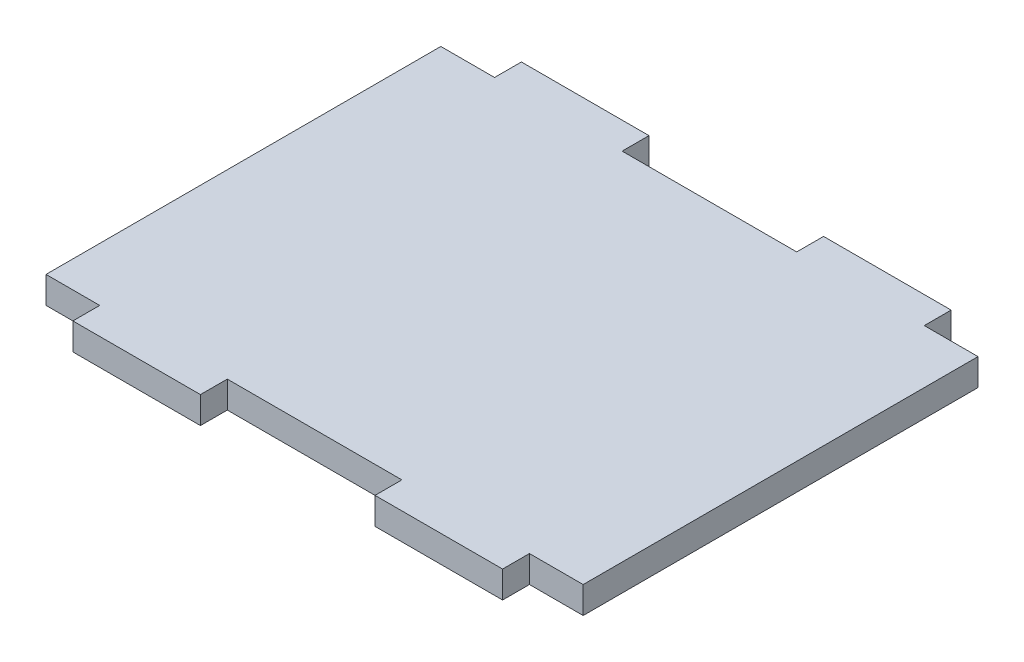
SolidWorks part; units mm, degrees
ref_plane "Front" through (0, 0, 0) normal (0, 0, 1) x (1, 0, 0)
ref_plane "Top" through (0, 0, 0) normal (0, 1, 0) x (1, 0, 0)
ref_plane "Right" through (0, 0, 0) normal (1, 0, 0) x (0, 0, -1)
sketch "Sketch1" plane through (0, 0, 0) normal (0, 1, 0) x (1, 0, 0)
  line L0 (-16, 16.7) -> (-16, 14.7)
  line L1 (20, -16.7) -> (-20, -16.7)
  line L2 (20, -16.7) -> (20, 16.7)
  line L3 (20, 16.7) -> (-20, 16.7)
  line L4 (-20, -16.7) -> (-20, 16.7)
  line L5 (20, -16.7) -> (-20, 16.7) construction
  line L6 (20, 16.7) -> (-20, -16.7) construction
  line L7 (-20, 16.7) -> (20, 16.7)
  line L8 (-20, 16.7) -> (-20, 14.7)
  line L9 (-20, 14.7) -> (20, 14.7)
  line L10 (20, 16.7) -> (20, 14.7)
  line L11 (0, 14.7) -> (0, 16.7) construction
  line L12 (-20, 15.7) -> (20, 15.7) construction
  line L13 (-6.5, 16.7) -> (-6.5, 14.7)
  line L14 (0, 0) -> (-20, 0) construction
  line L15 (0, 0) -> (0, -16.7) construction
  line L16 (6.5, 16.7) -> (6.5, 14.7)
  line L17 (16, 16.7) -> (16, 14.7)
  line L18 (16, -16.7) -> (16, -14.7)
  line L19 (6.5, -16.7) -> (6.5, -14.7)
  line L20 (-6.5, -16.7) -> (-6.5, -14.7)
  line L21 (-16, -16.7) -> (-16, -14.7)
  line L22 (-20, -14.7) -> (20, -14.7)
  point P0 (0, 0)
  point P120 (0, 15.7)
  dimension "D1" = 40
  dimension "D2" = 33.4
  dimension "D3" = 2
  dimension "D4" = 4
  dimension "D5" = 9.5
extrude "Boss-Extrude1" add sketch "Sketch1" along normal blind 2 contours L4 L22 L2 L9 | L13 L7 L0 L9 | L17 L7 L16 L9 | L22 L21 L1 L20 | L22 L19 L1 L18
